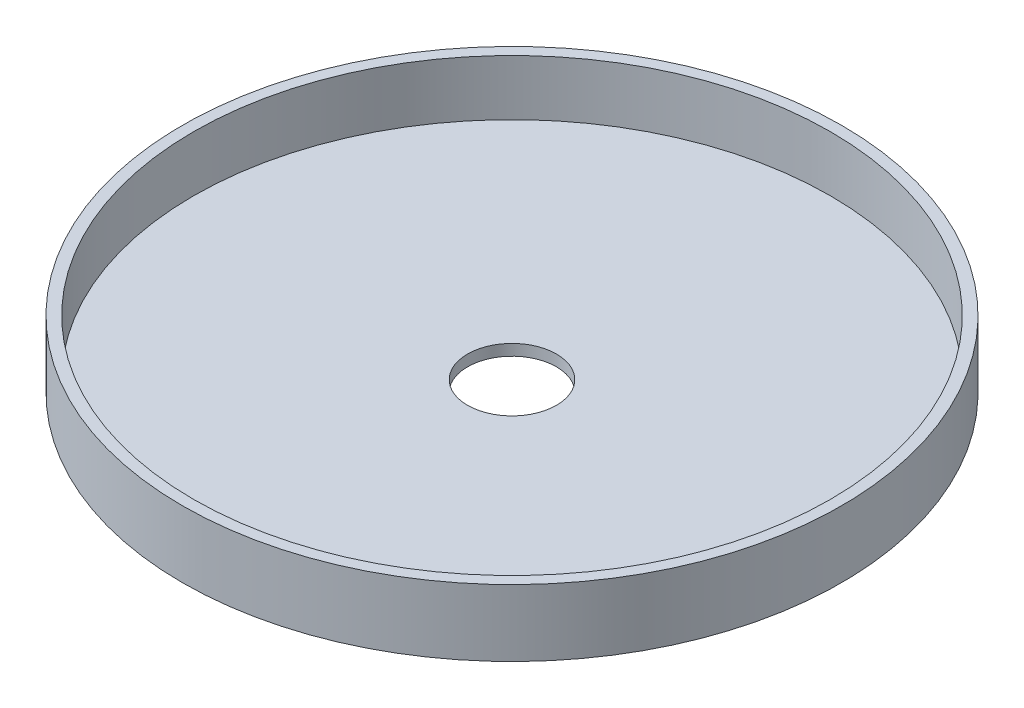
SolidWorks part; units mm, degrees
ref_plane "Спереди" through (0, 0, 0) normal (0, 0, 1) x (1, 0, 0)
ref_plane "Сверху" through (0, 0, 0) normal (0, 1, 0) x (1, 0, 0)
ref_plane "Справа" through (0, 0, 0) normal (1, 0, 0) x (0, 0, -1)
sketch "Эскиз1" plane through (0, 0, 0) normal (0, 1, 0) x (1, 0, 0)
  circle A0 centre (0, 0) radius 44.5
  dimension "D1" = 89
extrude "Бобышка-Вытянуть1" add sketch "Эскиз1" along normal blind 1.5
sketch "Эскиз2" plane through (0, 1.5, 0) normal (0, 1, 0) x (1, 0, 0)
  circle A0 centre (0, 0) radius 44.5
  circle A1 centre (0, 0) radius 43
  circle A2 centre (0, 0) radius 44.5 construction
  dimension "D1" = 1.5
extrude "Бобышка-Вытянуть2" add sketch "Эскиз2" along normal blind 7.5
sketch "Эскиз3" plane through (0, 0, 0) normal (0, -1, 0) x (1, 0, 0)
  circle A0 centre (0, 0) radius 6
  point P2 (0, 0)
  dimension "D1" = 12
extrude "Вырез-Вытянуть1" cut sketch "Эскиз3" against normal through all
